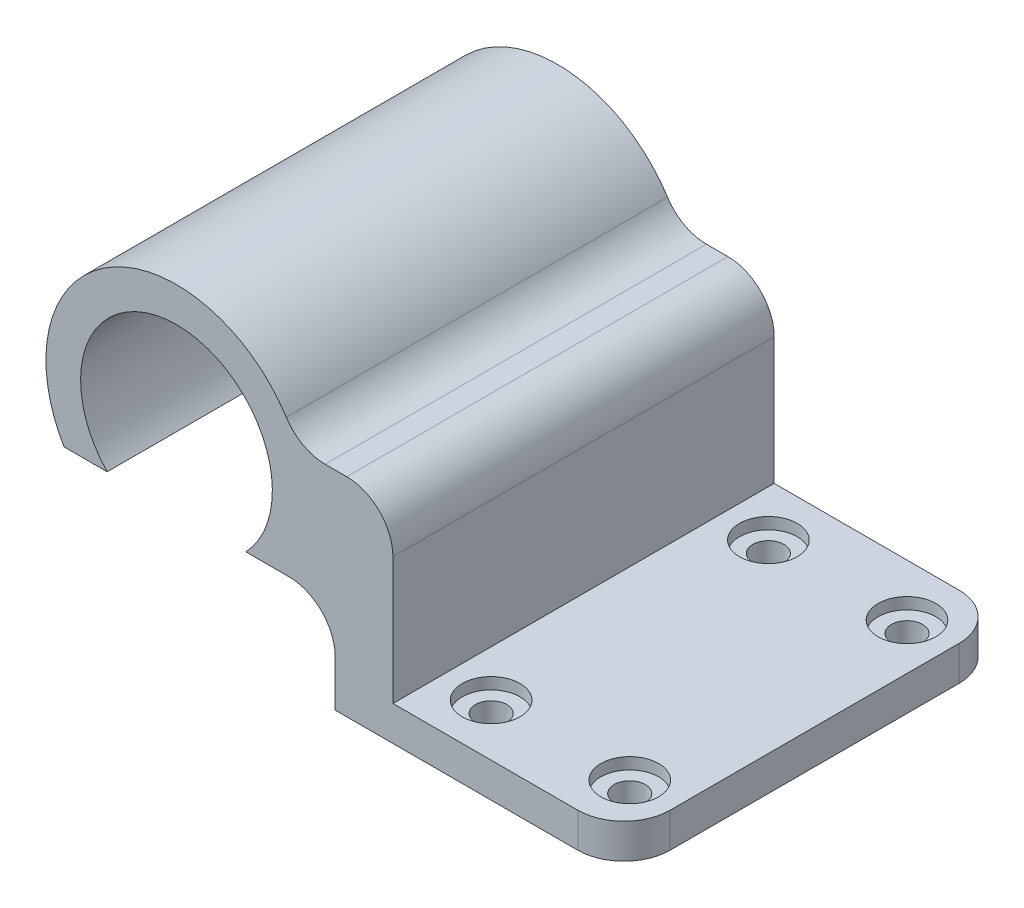
SolidWorks part; units mm, degrees
ref_plane "Front Plane" through (0, 0, 0) normal (0, 0, 1) x (1, 0, 0)
ref_plane "Top Plane" through (0, 0, 0) normal (0, 1, 0) x (1, 0, 0)
ref_plane "Right Plane" through (0, 0, 0) normal (1, 0, 0) x (0, 0, -1)
sketch "Sketch1" plane through (0, 0, 0) normal (0, 0, 1) x (1, 0, 0)
  line L0 (-6, -5.735) -> (6, -5.735) construction
  line L1 (-6, -5.735) -> (-9.7365, -5.735) construction
  line L2 (6, -5.735) -> (9.7365, -5.735) construction
  line L3 (-9.7365, -5.735) -> (-6, -5.735)
  line L4 (6, -5.735) -> (9.7365, -5.735)
  line L5 (9.7365, -5.735) -> (9.6743, -5.575)
  arc A0 (6, -5.735) -> (-6, -5.735) centre (0, 0) ccw
  arc A1 (9.7365, -5.735) -> (-9.7365, -5.735) centre (0, 0) ccw
  dimension "D1" = 16.6
  dimension "D2" = 3
  dimension "D3" = 12
extrude "Boss-Extrude1" add sketch "Sketch1" along normal blind 33
sketch "Sketch2" plane through (0, 0, 0) normal (0, 0, -1) x (-1, 0, 0)
  line L0 (-10.4642, 4.265) -> (-18.7365, 4.265)
  line L1 (-18.7365, 4.265) -> (-18.7365, -10.735)
  line L2 (-18.7365, -10.735) -> (-38.7365, -10.735)
  line L3 (-38.7365, -10.735) -> (-38.7365, -13.735)
  line L4 (-38.7365, -13.735) -> (-13.7365, -13.735)
  line L5 (-13.7365, -13.735) -> (-13.7365, -5.735)
  line L6 (-13.7365, -5.735) -> (-9.7365, -5.735)
  line L7 (-6, -5.735) -> (-9.7365, -5.735) construction
  arc A0 (9.7365, -5.735) -> (-9.7365, -5.735) centre (0, 0) ccw construction
  arc A1 (-10.4642, 4.265) -> (-9.7365, -5.735) centre (0, 0) ccw
  point P13 (-26.2907, -15.5952)
  point P14 (-54.229, -14.3754)
  point P15 (-15.229, 1.265)
  point P16 (0, 0)
  point P17 (-14.0645, -5.1377)
  point P18 (0, 0)
  point P20 (0, 0)
  point P21 (0, 0)
  dimension "D1" = 10
  dimension "D2" = 3
  dimension "D3" = 5
  dimension "D5" = 4
  dimension "D6" = 20
extrude "Boss-Extrude2" add sketch "Sketch2" against normal up to surface (33 mm away) up to face at (0, 2.0325, 33)
fillet "Fillet1" radius 4 2 edges at (10.4642, 4.265, 16.5) (18.7365, 4.265, 16.5)
fillet "Fillet3" radius 4 1 edges at (13.7365, -5.735, 16.5)
sketch "Sketch3" plane through (0, -10.735, 0) normal (0, 1, 0) x (1, 0, 0)
  line L0 (22.7365, -4.5) -> (22.7365, -28.5) construction
  line L1 (34.7365, -4.5) -> (34.7365, -28.5) construction
  line L2 (38.7365, -33) -> (38.7365, 0) construction
  circle A0 centre (22.7365, -4.5) radius 1.35
  circle A1 centre (34.7365, -4.5) radius 1.35
  circle A2 centre (34.7365, -28.5) radius 1.35
  circle A3 centre (22.7365, -28.5) radius 1.35
  point P2 (34.7365, -16.5)
  point P11 (38.7365, -16.5)
  dimension "D4" = 2.7
  dimension "D3" = 4
  dimension "D1" = 2
  dimension "D2" = 2
extrude "Cut-Extrude1" cut sketch "Sketch3" against normal blind 10
sketch "Sketch4" plane through (0, -10.735, 0) normal (0, 1, 0) x (1, 0, 0)
  circle A0 centre (22.7365, -28.5) radius 2.5
  circle A1 centre (34.7365, -28.5) radius 2.5
  circle A2 centre (34.7365, -4.5) radius 2.5
  circle A3 centre (22.7365, -4.5) radius 2.5
  dimension "D1" = 5
  dimension "D2" = 2
  dimension "D3" = 2
extrude "Cut-Extrude2" cut sketch "Sketch4" against normal blind 1
fillet "Fillet4" radius 4 2 edges at (38.7365, -12.235, 33) (38.7365, -12.235, 0)
